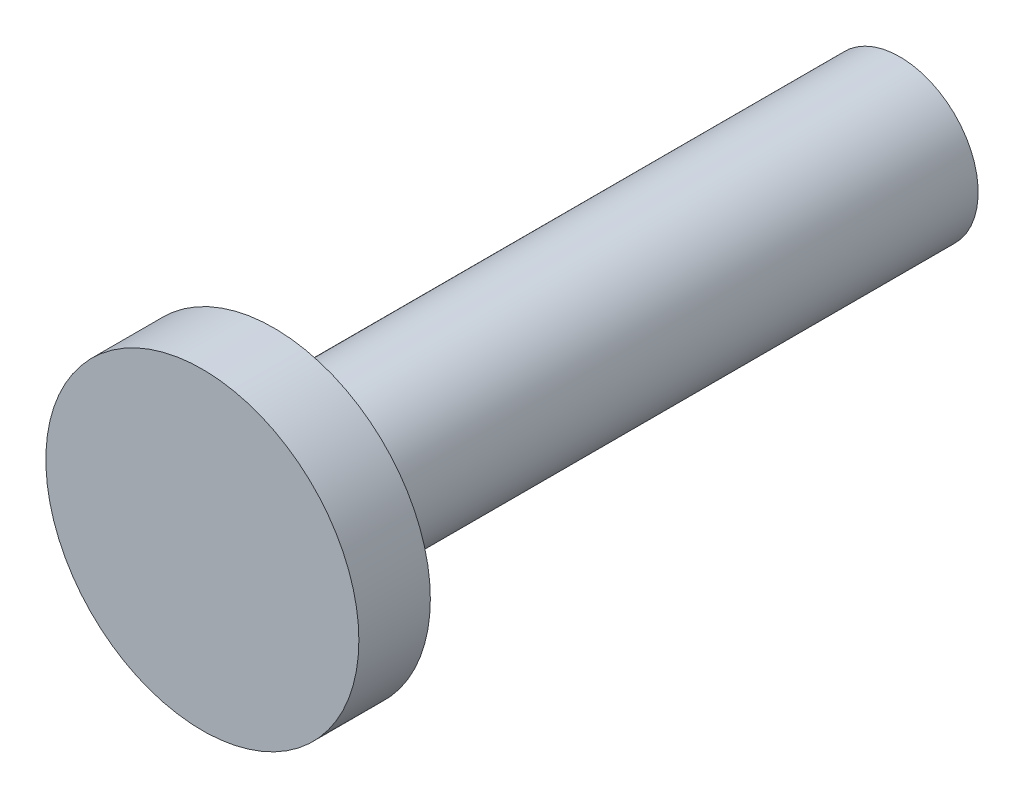
SolidWorks part; units mm, degrees
ref_plane "Plan de face" through (0, 0, 0) normal (0, 0, 1) x (1, 0, 0)
ref_plane "Plan de dessus" through (0, 0, 0) normal (0, 1, 0) x (1, 0, 0)
ref_plane "Plan de droite" through (0, 0, 0) normal (1, 0, 0) x (0, 0, -1)
sketch "Esquisse1" plane through (0, 0, 0) normal (0, 0, 1) x (1, 0, 0)
  circle A0 centre (0, 0) radius 3
  dimension "D1" = 6
extrude "Boss.-Extru.1" add sketch "Esquisse1" along normal blind 1.37
sketch "Esquisse2" plane through (0, 0, 0) normal (0, 0, -1) x (-1, 0, 0)
  circle A0 centre (0, 0) radius 1.5
  dimension "D1" = 3
extrude "Boss.-Extru.2" add sketch "Esquisse2" along normal blind 12
